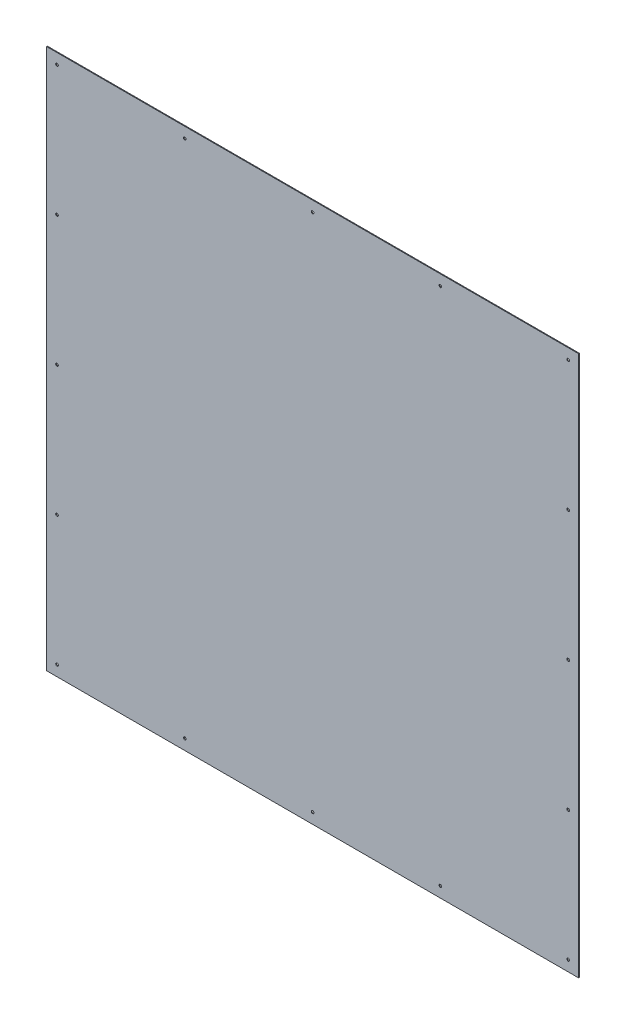
SolidWorks part; units mm, degrees
ref_plane "Alzado" through (0, 0, 0) normal (0, 0, 1) x (1, 0, 0)
ref_plane "Planta" through (0, 0, 0) normal (0, 1, 0) x (1, 0, 0)
ref_plane "Vista lateral" through (0, 0, 0) normal (1, 0, 0) x (0, 0, -1)
sketch "Croquis1" plane through (0, 0, 0) normal (0, 0, 1) x (1, 0, 0)
  line L1 (-640, 650) -> (640, 650)
  line L2 (-640, 650) -> (-640, -650)
  line L3 (-640, -650) -> (640, -650)
  line L4 (640, 650) -> (640, -650)
  line L5 (-640, 650) -> (640, -650) construction
  line L6 (-640, -650) -> (640, 650) construction
  point P0 (0, 0)
  dimension "D1" = 1280
  dimension "D2" = 1300
extrude "Saliente-Extruir1" add sketch "Croquis1" along normal blind 1.9
sketch "Croquis2" plane through (0, 0, 1.9) normal (0, 0, 1) x (1, 0, 0)
  line L0 (-640, -650) -> (640, -650) construction
  line L1 (614.6, -624.6) -> (-614.6, -624.6) construction
  line L2 (614.6, -624.6) -> (614.6, 624.6) construction
  line L3 (614.6, 624.6) -> (-614.6, 624.6) construction
  line L4 (-614.6, -624.6) -> (-614.6, 624.6) construction
  line L5 (614.6, -624.6) -> (-614.6, 624.6) construction
  line L6 (614.6, 624.6) -> (-614.6, -624.6) construction
  line L7 (-640, 650) -> (-640, -650) construction
  line L8 (0, 0) -> (-614.6, 0) construction
  line L9 (0, 0) -> (0, -624.6) construction
  line L10 (0, -624.6) -> (614.6, -624.6) construction
  line L11 (614.6, -624.6) -> (307.3, -624.6) construction
  line L12 (307.3, -624.6) -> (307.3, 624.6) construction
  line L13 (-614.6, -624.6) -> (-614.6, 0) construction
  line L14 (-614.6, 0) -> (-614.6, -312.3) construction
  line L15 (-614.6, 0) -> (-614.6, 624.6) construction
  line L16 (-614.6, 624.6) -> (-614.6, 312.3) construction
  circle A0 centre (-614.6, -624.6) radius 3.175
  circle A1 centre (-614.6, 624.6) radius 3.175
  circle A2 centre (614.6, 624.6) radius 3.175
  circle A3 centre (614.6, -624.6) radius 3.175
  circle A4 centre (0, -624.6) radius 3.175
  circle A5 centre (0, 624.6) radius 3.175
  circle A6 centre (307.3, -624.6) radius 3.175
  circle A7 centre (307.3, 624.6) radius 3.175
  circle A8 centre (-307.3, 624.6) radius 3.175
  circle A9 centre (-307.3, -624.6) radius 3.175
  circle A10 centre (-614.6, -312.3) radius 3.175
  circle A11 centre (-614.6, 0) radius 3.175
  circle A12 centre (-614.6, 312.3) radius 3.175
  circle A13 centre (614.6, 312.3) radius 3.175
  circle A14 centre (614.6, 0) radius 3.175
  circle A15 centre (614.6, -312.3) radius 3.175
  point P0 (0, 0)
  dimension "D3" = 6.35
  dimension "D4" = 6.35
  dimension "D5" = 6.35
  dimension "D6" = 6.35
  dimension "D7" = 6.35
  dimension "D8" = 6.35
  dimension "D1" = 25.4
  dimension "D2" = 25.4
extrude "Cortar-Extruir2" cut sketch "Croquis2" against normal blind 120
